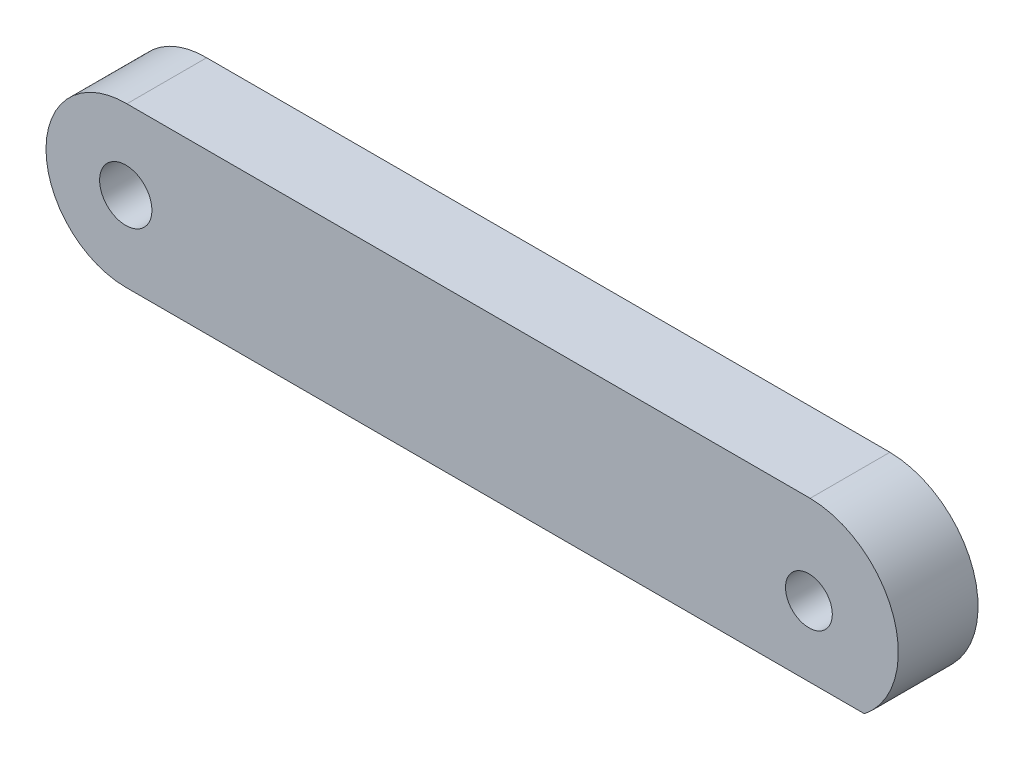
SolidWorks part; units mm, degrees
material "Custom Plastic"
ref_plane "Front Plane" through (0, 0, 0) normal (0, 0, 1) x (1, 0, 0)
ref_plane "Top Plane" through (0, 0, 0) normal (0, 1, 0) x (1, 0, 0)
ref_plane "Right Plane" through (0, 0, 0) normal (1, 0, 0) x (0, 0, -1)
sketch "Sketch1" plane through (0, 0, 57.7878) normal (0, 0, 1) x (1, 0, 0)
  line L1 (-62.8588, 13.1002) -> (-62.9013, 10.1005) construction
  line L2 (-62.8162, 16.1099) -> (-90.0205, 16.1099)
  line L3 (-89.788, 32.533) -> (-91.0105, -53.8183) construction
  line L4 (-90.0655, 9.7603) -> (-60.6552, 9.7603)
  circle A0 centre (-62.8666, 12.5502) radius 0.9316
  circle A1 centre (-90.0655, 12.9353) radius 3.175 construction
  arc A2 (-90.0205, 16.1099) -> (-90.0655, 9.7603) centre (-90.0655, 12.9353) ccw
  arc A3 (-62.8162, 16.1099) -> (-60.6552, 9.7603) centre (-62.8666, 12.5502) cw
  circle A4 centre (-90.0655, 12.9353) radius 1.0414
extrude "Boss-Extrude1" add sketch "Sketch1" along normal blind 3.175
